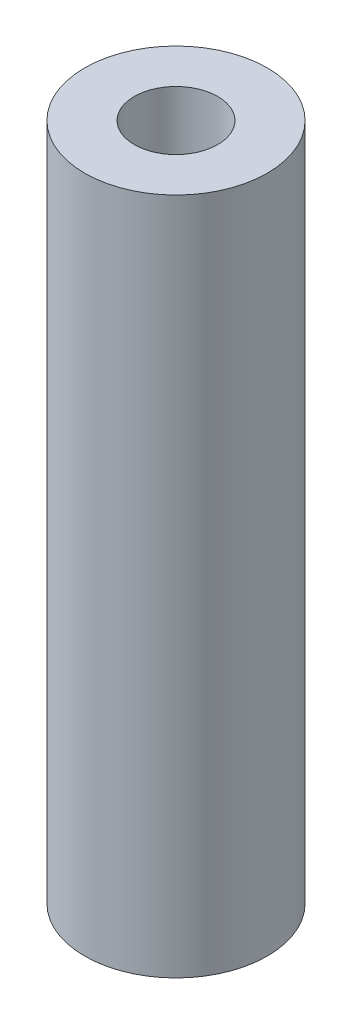
SolidWorks part; units mm, degrees
ref_plane "Front Plane" through (0, 0, 0) normal (0, 0, 1) x (1, 0, 0)
ref_plane "Top Plane" through (0, 0, 0) normal (0, 1, 0) x (1, 0, 0)
ref_plane "Right Plane" through (0, 0, 0) normal (1, 0, 0) x (0, 0, -1)
sketch "Sketch1" plane through (0, 0, 0) normal (0, 1, 0) x (1, 0, 0)
  circle A0 centre (0, 0) radius 3.5
  circle A1 centre (0, 0) radius 1.6
  dimension "D1" = 7
  dimension "D2" = 3.2
extrude "Boss-Extrude1" add sketch "Sketch1" along normal blind 26
